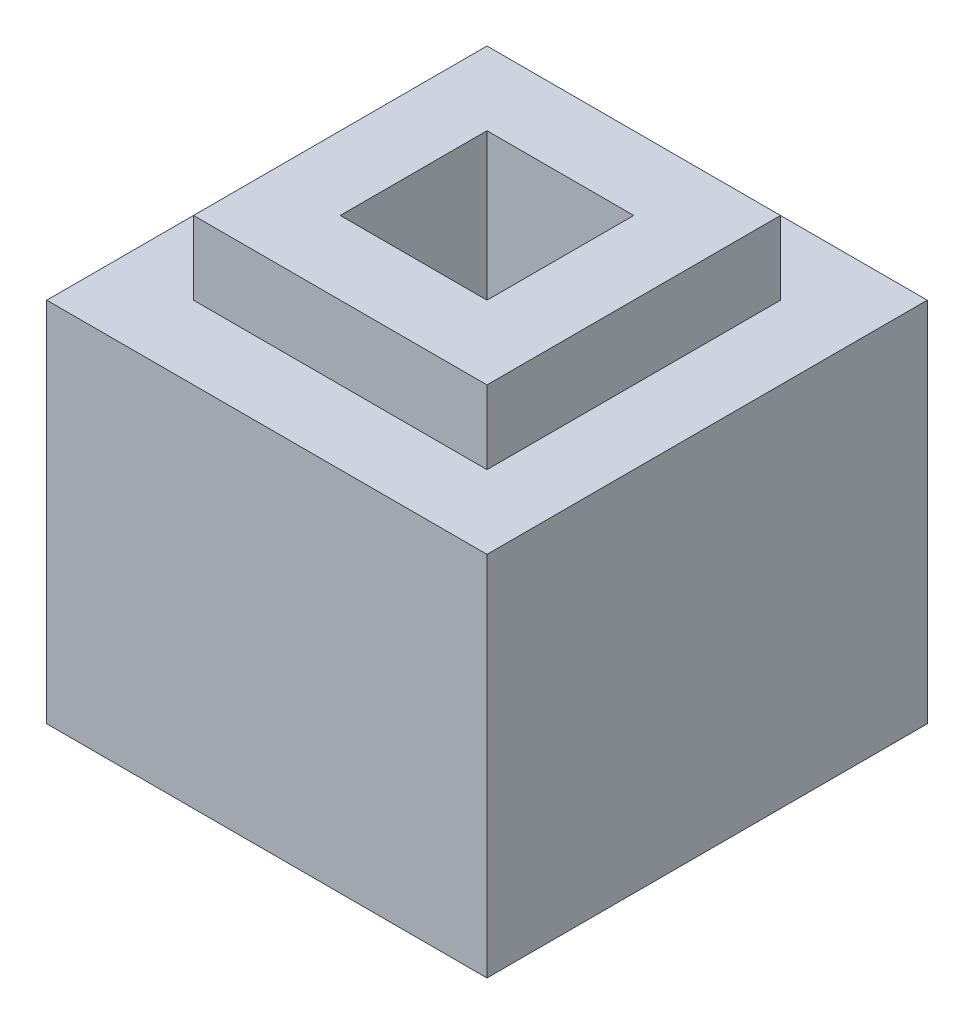
SolidWorks part; units mm, degrees
ref_plane "Front Plane" through (0, 0, 0) normal (0, 0, 1) x (1, 0, 0)
ref_plane "Top Plane" through (0, 0, 0) normal (0, 1, 0) x (1, 0, 0)
ref_plane "Right Plane" through (0, 0, 0) normal (1, 0, 0) x (0, 0, -1)
sketch "Sketch1" plane through (0, 0, 0) normal (0, 1, 0) x (1, 0, 0)
  line L1 (0, 0) -> (30, 0)
  line L2 (0, 0) -> (0, 30)
  line L3 (0, 30) -> (30, 30)
  line L4 (30, 0) -> (30, 30)
  point P5 (30, 15)
  dimension "D1" = 30
  dimension "D2" = 30
extrude "Boss-Extrude1" add sketch "Sketch1" along normal blind 25
sketch "Sketch3" plane through (0, 25, 0) normal (0, 1, 0) x (1, 0, 0)
  line L0 (0, 0) -> (30, 0) construction
  line L1 (10, 10) -> (20, 10)
  line L2 (10, 10) -> (10, 20)
  line L3 (10, 20) -> (20, 20)
  line L4 (20, 10) -> (20, 20)
  line L5 (0, 30) -> (0, 0) construction
  point P8 (15, 10)
  dimension "D1" = 10
  dimension "D2" = 10
  dimension "D3" = 10
  dimension "D4" = 10
extrude "Cut-Extrude1" cut sketch "Sketch3" against normal blind 20
sketch "Sketch4" plane through (0, 0, 0) normal (-1, 0, 0) x (0, 0, 1)
  line L0 (0, 25) -> (0, 0) construction
  line L1 (-30, 25) -> (0, 25) construction
  circle A0 centre (-15, 10) radius 8
  point P6 (-15, 25)
  dimension "D1" = 15
  dimension "D3" = 16
  dimension "D2" = 15
extrude "Cut-Extrude2" cut sketch "Sketch4" against normal blind 15
sketch "Sketch5" plane through (0, 25, 0) normal (0, 1, 0) x (1, 0, 0)
  line L0 (20, 20) -> (10, 20) construction
  line L1 (5, 25) -> (25, 25)
  line L2 (5, 25) -> (5, 5)
  line L3 (5, 5) -> (25, 5)
  line L4 (25, 25) -> (25, 5)
  line L6 (10, 10) -> (20, 10) construction
  line L7 (20, 10) -> (20, 20) construction
  line L8 (10, 20) -> (10, 10) construction
  dimension "D1" = 5
  dimension "D2" = 5
  dimension "D3" = 5
  dimension "D4" = 5
extrude "Boss-Extrude2" add sketch "Sketch5" along normal blind 5
sketch "Sketch6" plane through (0, 30, 0) normal (0, 1, 0) x (1, 0, 0)
  line L0 (5, 25) -> (5, 5) construction
  line L1 (10, 20) -> (20, 20)
  line L2 (10, 20) -> (10, 10)
  line L3 (10, 10) -> (20, 10)
  line L4 (20, 20) -> (20, 10)
  line L5 (25, 5) -> (25, 25) construction
  line L6 (5, 5) -> (25, 5) construction
  point P4 (20, 15)
  dimension "D1" = 10
  dimension "D2" = 10
  dimension "D3" = 5
  dimension "D4" = 5
  dimension "D5" = 5
extrude "Cut-Extrude3" cut sketch "Sketch6" against normal blind 15
